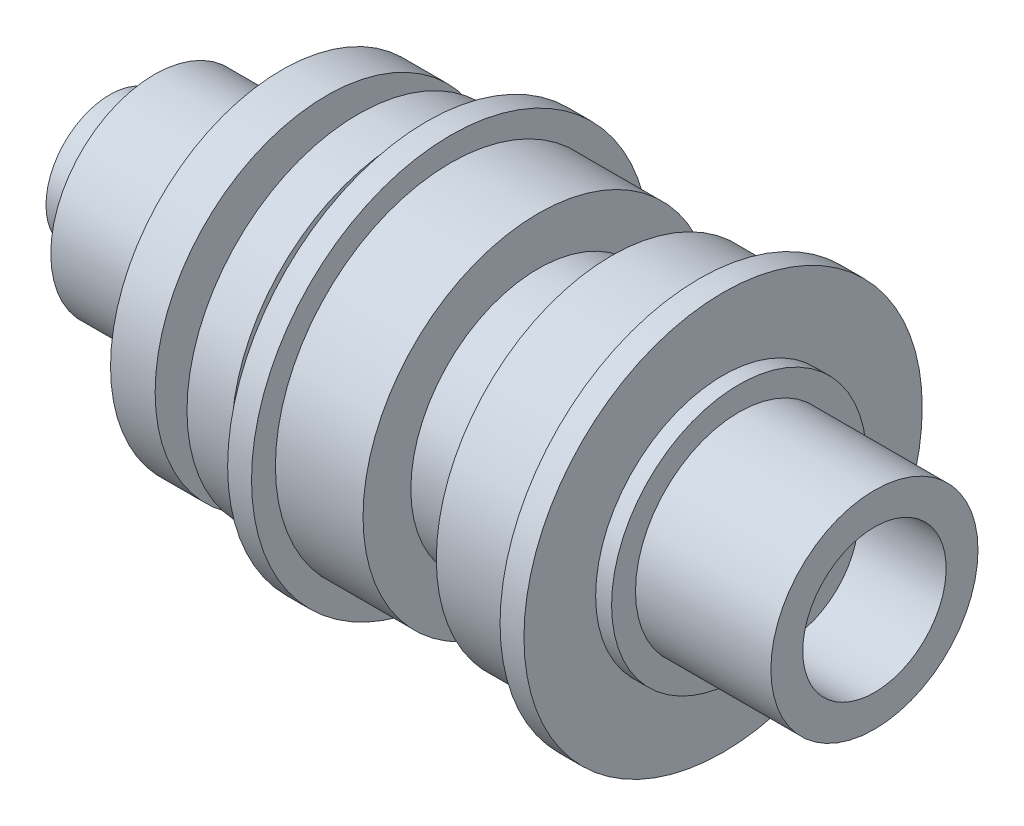
SolidWorks part; units mm, degrees
material "Chrome Stainless Steel"
ref_plane "Front Plane" through (0, 0, 0) normal (0, 0, 1) x (1, 0, 0)
ref_plane "Top Plane" through (0, 0, 0) normal (0, 1, 0) x (1, 0, 0)
ref_plane "Right Plane" through (0, 0, 0) normal (1, 0, 0) x (0, 0, -1)
sketch "Sketch1" plane through (0, 0, 0) normal (0, 0, 1) x (1, 0, 0)
  line L0 (10.8, 6.5) -> (2.8, 6.5)
  line L1 (0, -55) -> (0, 55) construction
  line L2 (10.8, 6.5) -> (10.8, 10.75)
  line L3 (10.8, 10.75) -> (13.6, 10.75)
  line L4 (13.6, 10.75) -> (13.6, 4)
  line L5 (13.6, 4) -> (15.6, 4)
  line L6 (15.6, 4) -> (15.6, 10.75)
  line L7 (15.6, 10.75) -> (18.4, 10.75)
  line L8 (18.4, 10.75) -> (18.4, 8)
  line L9 (18.4, 8) -> (19.9, 8)
  line L10 (19.9, 8) -> (19.9, 12.5)
  line L11 (19.9, 12.5) -> (21.4, 12.5)
  line L12 (21.4, 12.5) -> (21.4, 11)
  line L13 (21.4, 11) -> (26.9, 11)
  line L14 (26.9, 11) -> (26.9, 8)
  line L15 (26.9, 8) -> (31.5, 8)
  line L16 (31.5, 8) -> (31.5, 11)
  line L17 (31.5, 11) -> (37, 11)
  line L18 (37, 11) -> (37, 12.5)
  line L19 (37, 12.5) -> (38.5, 12.5)
  line L20 (38.5, 12.5) -> (38.5, 8)
  line L21 (38.5, 8) -> (39.5, 8)
  line L22 (39.5, 8) -> (39.5, 6.5)
  line L23 (39.5, 6.5) -> (48, 6.5)
  line L24 (48, 6.5) -> (48, 4.5)
  line L25 (55, 0) -> (-55, 0) construction
  line L26 (42.5, 0) -> (0, 0)
  line L27 (0, 0) -> (0, 4)
  line L28 (-10.6952, 0) -> (75.9162, 0) construction
  line L29 (48, 4.5) -> (42.5, 4.5)
  line L30 (42.5, 4.5) -> (42.5, 0)
  line L31 (2.8, 6.5) -> (2.8, 4)
  line L32 (2.8, 4) -> (0, 4)
  dimension "D1" = 4
  dimension "D2" = 7
  dimension "D3" = 7
  dimension "D4" = 15.6
  dimension "D5" = 1.5
  dimension "D6" = 1.5
  dimension "D7" = 1
  dimension "D8" = 9.5
  dimension "D9" = 6.5
  dimension "D10" = 8
  dimension "D11" = 11
  dimension "D12" = 10.75
  dimension "D13" = 12.5
  dimension "D14" = 2.8
  dimension "D15" = 48
  dimension "D16" = 2
  dimension "D17" = 1.5
  dimension "D18" = 5.5
  dimension "D19" = 2
  dimension "D21" = 8
revolve "Revolve1" add sketch "Sketch1" angle 360 about L28
